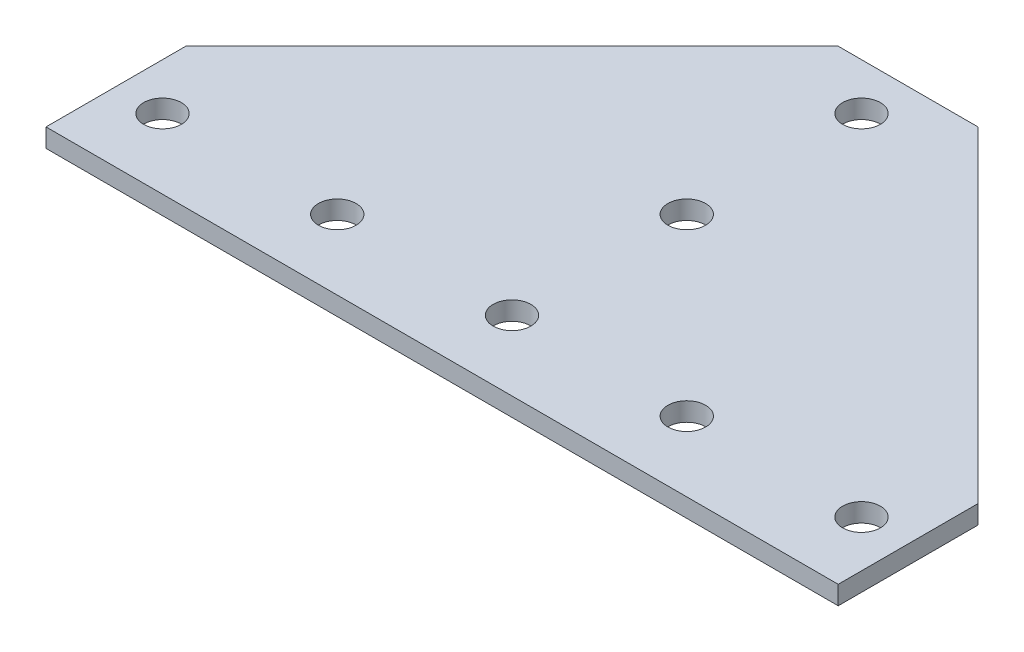
SolidWorks part; units mm, degrees
material "6061-T6 (SS)"
ref_plane "Front Plane" through (0, 0, 0) normal (0, 0, 1) x (1, 0, 0)
ref_plane "Top Plane" through (0, 0, 0) normal (0, 1, 0) x (1, 0, 0)
ref_plane "Right Plane" through (0, 0, 0) normal (1, 0, 0) x (0, 0, -1)
sketch "Sketch1" plane through (0, 0, 0) normal (0, 1, 0) x (1, 0, 0)
  line L0 (0, 0) -> (-75, 0) construction
  line L1 (0, 0) -> (0, 75) construction
  line L2 (85, -15) -> (-85, -15)
  line L4 (-85, -15) -> (-85, 15)
  line L5 (-85, 15) -> (-15, 85)
  line L6 (-15, 85) -> (15, 85)
  line L7 (0, 0) -> (75, 0) construction
  line L8 (15, 85) -> (85, 15)
  line L9 (85, 15) -> (85, -15)
  circle A0 centre (-75, 0) radius 4.05
  circle A1 centre (-37.5, 0) radius 4.05
  circle A2 centre (0, 0) radius 4.05
  circle A3 centre (0, 75) radius 4.05
  circle A4 centre (0, 37.5) radius 4.05
  circle A5 centre (75, 0) radius 4.05
  circle A6 centre (37.5, 0) radius 4.05
  point P21 (0, 0)
  point P22 (0, 0)
  point P23 (0, 85)
  dimension "D1" = 8.1
  dimension "D2" = 75
  dimension "D3" = 15
  dimension "D4" = 10
  dimension "D5" = 30
  dimension "D6" = 10
  dimension "D7" = 30
  dimension "D8" = 10
extrude "Boss-Extrude1" add sketch "Sketch1" along normal blind 4
